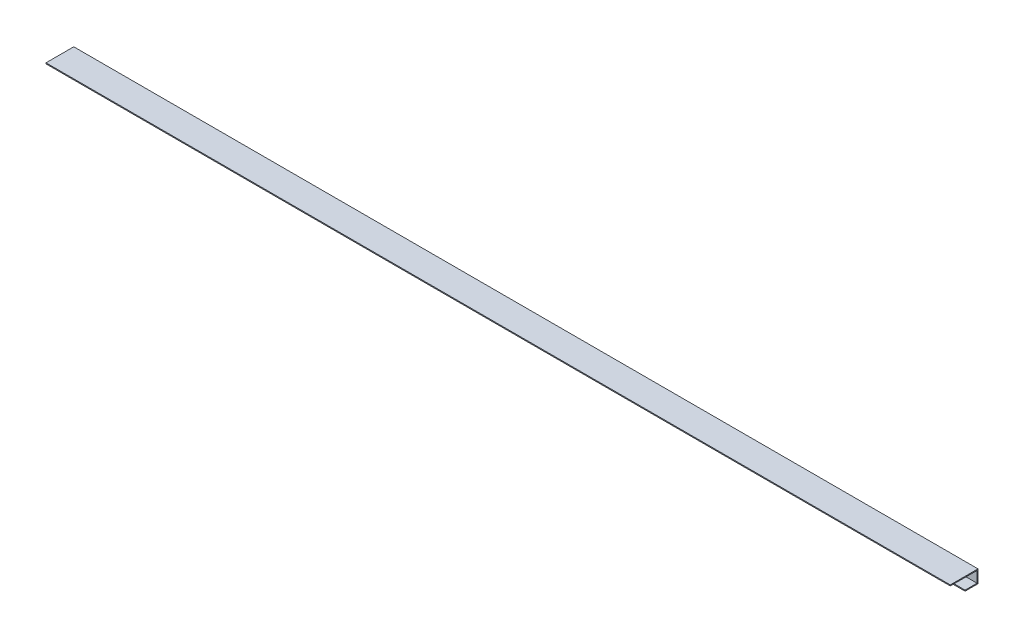
SolidWorks part; units mm, degrees
ref_plane "Front Plane" through (0, 0, 0) normal (0, 0, 1) x (1, 0, 0)
ref_plane "Top Plane" through (0, 0, 0) normal (0, 1, 0) x (1, 0, 0)
ref_plane "Right Plane" through (0, 0, 0) normal (1, 0, 0) x (0, 0, -1)
sketch "Sketch1" plane through (0, 0, 0) normal (1, 0, 0) x (0, 0, -1)
  line L0 (0, 0) -> (58, 0)
  line L1 (58, 0) -> (58, -27)
  line L2 (58, -27) -> (31, -27)
  line L3 (0, -2) -> (56, -2)
  line L4 (56, -2) -> (56, -25)
  line L5 (56, -25) -> (31, -25)
  line L6 (0, 0) -> (0, -2)
  line L7 (31, -25) -> (31, -27)
  dimension "D1" = 2
  dimension "D2" = 58
  dimension "D3" = 27
  dimension "D4" = 27
extrude "Boss-Extrude1" add sketch "Sketch1" along normal blind 1890
equation "\"door_base_short7_R1_L_open_Single_height\"=1890.0"
equation "\"D1@Boss-Extrude1\"=\"door_base_short7_R1_L_open_Single_height\""
equation "\"CarBeamWidth\"=700.0"
equation "\"WheelWidth\"=650.0"
equation "\"Wheel_FrontBoxDistance\"=1390.0"
equation "\"MetalSheet_3mm_length\"=5030.0"
equation "\"MetalSheet_3mm_width\"=1923.0"
equation "\"MetalSheet_3mm_FloorCut_L_length\"=1764.0"
equation "\"MetalSheet_3mm_FloorCut_L_disdance\"=1665.0"
equation "\"MetalSheet_3mm_FloorCut_R_length\"=1764.0"
equation "\"MetalSheet_3mm_FloorCut_R_disdance\"=1665.0"
equation "\"indoorHeight\"=1940.0"
equation "\"haveDoor_R\"=1"
equation "\"side_door_bottom_R_3mm_length\"=1934.0"
equation "\"1Bar_Side_RF_3mm_length\"=1493.0"
equation "\"1Bar_Side_RB_3mm_length\"=1493.0"
equation "\"DoorSeparator_RF_3mm_withHinge_toFrontDistance\"=1673.0"
equation "\"DoorSeparator_RF_3mm_withHinge_exist\"=1"
equation "\"DoorSeparator_RB_3mm_withHinge_toFrontDistance\"=3427.0"
equation "\"DoorSeparator_RB_3mm_withHinge_exist\"=1"
equation "\"Door_R1_L_open_Single_toFrontDistance\"=2547.5"
equation "\"Door_R1_L_open_Single_exist\"=1"
equation "\"door_base_long7_R1_L_open_Single_height\"=1890.0"
equation "\"door_base_short7_R1_L_open_Single_width\"=864"
equation "\"Door_R1_R_open_Single_toFrontDistance\"=3422.0"
equation "\"Door_R1_R_open_Single_exist\"=1"
equation "\"door_base_long7_R1_R_open_Single_height\"=1890.0"
equation "\"door_base_short7_R1_R_open_Single_height\"=1890.0"
equation "\"door_base_short7_R1_R_open_Single_width\"=864"
equation "\"x\"=66.0"
equation "\"da\"=62.0"
equation "\"SquareTube_length\"=1923.0"
equation "\"channelSteel_length\"=5030.0"
equation "\"SquareTube_inFront_AvgDistance\"=285.0"
equation "\"SquareTube_inFront_TotalCount\"=5"
equation "\"SquareTube_inFront1_cutDepth50_R\"=0.5"
equation "\"SquareTube_inFront1_cutDepth50_L\"=0.5"
equation "\"SquareTube_inFront2_cutDepth50_R\"=0.5"
equation "\"SquareTube_inFront2_cutDepth50_L\"=0.5"
equation "\"SquareTube_inFront3_cutDepth50_R\"=0.5"
equation "\"SquareTube_inFront3_cutDepth50_L\"=0.5"
equation "\"SquareTube_inFront4_cutDepth50_R\"=0.5"
equation "\"SquareTube_inFront4_cutDepth50_L\"=0.5"
equation "\"SquareTube_inFront5_cutDepth50_R\"=50"
equation "\"SquareTube_inFront5_cutDepth50_L\"=50"
equation "\"SquareTube_inFront6_cutDepth50_R\"=50"
equation "\"SquareTube_inFront6_cutDepth50_L\"=50"
equation "\"SquareTube_inFront7_cutDepth50_R\"=50"
equation "\"SquareTube_inFront7_cutDepth50_L\"=50"
equation "\"SquareTube_inFront8_cutDepth50_R\"=50"
equation "\"SquareTube_inFront8_cutDepth50_L\"=50"
equation "\"SquareTube_inFront9_cutDepth50_R\"=50"
equation "\"SquareTube_inFront9_cutDepth50_L\"=50"
equation "\"SquareTube_inFront10_cutDepth50_R\"=50"
equation "\"SquareTube_inFront10_cutDepth50_L\"=50"
equation "\"SquareTube_inFront11_cutDepth50_R\"=50"
equation "\"SquareTube_inFront11_cutDepth50_L\"=50"
equation "\"SquareTube_inFront12_cutDepth50_R\"=50"
equation "\"SquareTube_inFront12_cutDepth50_L\"=50"
equation "\"SquareTube_inFront13_cutDepth50_R\"=50"
equation "\"SquareTube_inFront13_cutDepth50_L\"=50"
equation "\"SquareTube_inFront14_cutDepth50_R\"=50"
equation "\"SquareTube_inFront14_cutDepth50_L\"=50"
equation "\"SquareTube_inBack_AvgDistance\"=333.125"
equation "\"SquareTube_inBack_TotalCount\"=9"
equation "\"SquareTube_inBack1_cutDepth50_R\"=50"
equation "\"SquareTube_inBack1_cutDepth50_L\"=50"
equation "\"SquareTube_inBack2_cutDepth50_R\"=50"
equation "\"SquareTube_inBack2_cutDepth50_L\"=50"
equation "\"SquareTube_inBack3_cutDepth50_R\"=50"
equation "\"SquareTube_inBack3_cutDepth50_L\"=50"
equation "\"SquareTube_inBack4_cutDepth50_R\"=50"
equation "\"SquareTube_inBack4_cutDepth50_L\"=50"
equation "\"SquareTube_inBack5_cutDepth50_R\"=50"
equation "\"SquareTube_inBack5_cutDepth50_L\"=50"
equation "\"SquareTube_inBack6_cutDepth50_R\"=0.5"
equation "\"SquareTube_inBack6_cutDepth50_L\"=0.5"
equation "\"SquareTube_inBack7_cutDepth50_R\"=0.5"
equation "\"SquareTube_inBack7_cutDepth50_L\"=0.5"
equation "\"SquareTube_inBack8_cutDepth50_R\"=0.5"
equation "\"SquareTube_inBack8_cutDepth50_L\"=0.5"
